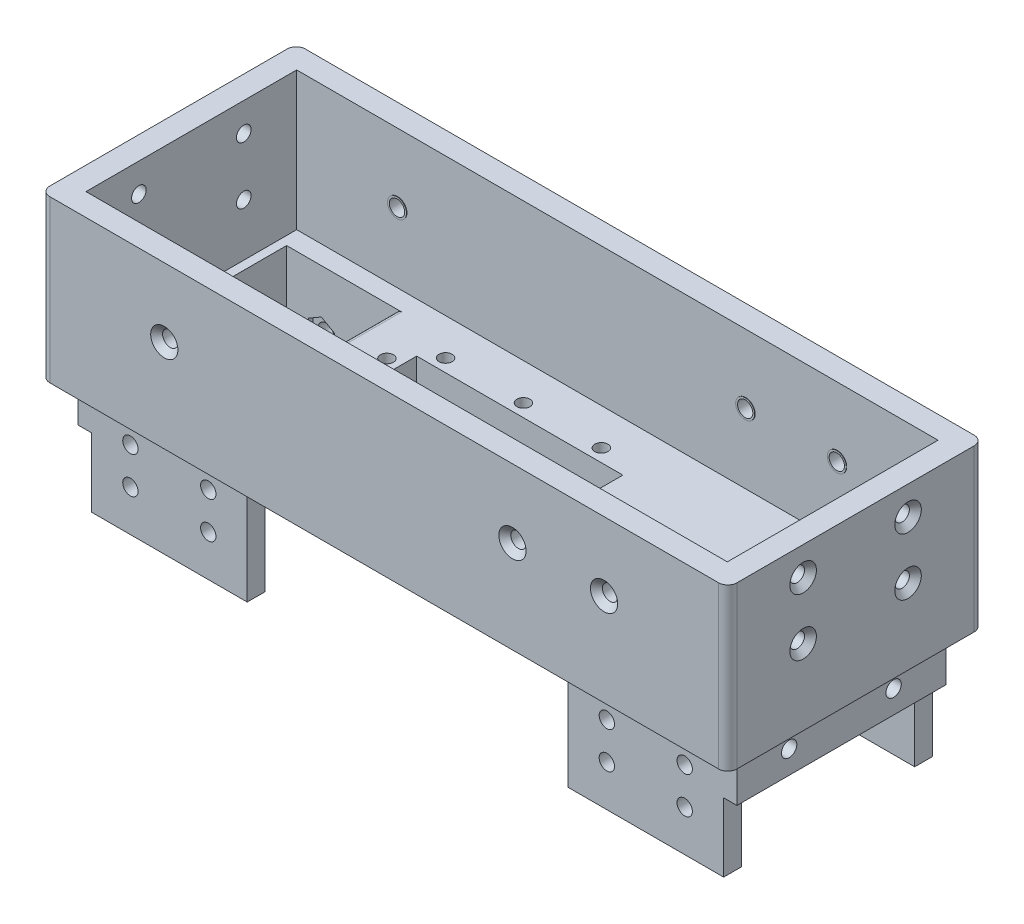
SolidWorks part; units mm, degrees
ref_plane "前视基准面" through (0, 0, 0) normal (0, 0, 1) x (1, 0, 0)
ref_plane "上视基准面" through (0, 0, 0) normal (0, 1, 0) x (1, 0, 0)
ref_plane "右视基准面" through (0, 0, 0) normal (1, 0, 0) x (0, 0, -1)
sketch "草图1" plane through (0, 0, 0) normal (0, 1, 0) x (1, 0, 0)
  line L1 (-75, 25.9) -> (75, 25.9)
  line L2 (-75, 25.9) -> (-75, -25.9)
  line L3 (-75, -25.9) -> (75, -25.9)
  line L4 (75, 25.9) -> (75, -25.9)
  line L5 (-75, 25.9) -> (75, -25.9) construction
  line L6 (-75, -25.9) -> (75, 25.9) construction
  line L7 (-70, 22.9) -> (70, 22.9)
  line L8 (-70, 22.9) -> (-70, -22.9)
  line L9 (-70, -22.9) -> (70, -22.9)
  line L10 (70, 22.9) -> (70, -22.9)
  line L11 (-70, 22.9) -> (70, -22.9) construction
  line L12 (-70, -22.9) -> (70, 22.9) construction
  point P0 (0, 0)
  point P5 (0, 0)
  dimension "D1" = 150
  dimension "D2" = 51.8
  dimension "D3" = 140
  dimension "D4" = 45.8
extrude "凸台-拉伸1" add sketch "草图1" along normal blind 35.2
sketch "草图2" plane through (0, 0, 0) normal (0, 1, 0) x (1, 0, 0)
  line L1 (-70, 22.9) -> (70, 22.9)
  line L2 (-70, 22.9) -> (-70, -22.9)
  line L3 (-70, -22.9) -> (70, -22.9)
  line L4 (70, 22.9) -> (70, -22.9)
  line L5 (-70, 22.9) -> (70, -22.9) construction
  line L6 (-70, -22.9) -> (70, 22.9) construction
  point P0 (0, 0)
extrude "凸台-拉伸2" add sketch "草图2" along normal blind 4.25 contours L1 L4 L3 L2
sketch "草图3" plane through (0, 0, 0) normal (0, 1, 0) x (1, 0, 0)
  line L1 (-33, 12.2) -> (12, 12.2)
  line L2 (-33, 12.2) -> (-33, -12.2)
  line L3 (-33, -12.2) -> (12, -12.2)
  line L4 (12, 12.2) -> (12, -12.2)
  dimension "D1" = 12
  dimension "D2" = 12.2
  dimension "D3" = 12.2
  dimension "D4" = 45
extrude "切除-拉伸2" cut sketch "草图3" along normal through all contours L3 L4 L1 L2
sketch "草图4" plane through (0, 0, 0) normal (0, 1, 0) x (1, 0, 0)
  circle A0 centre (4.5, 15) radius 1.425
  circle A1 centre (-12.5, 15) radius 1.425
  circle A2 centre (-29.5, 15) radius 1.425
  dimension "D1" = 2.85
  dimension "D2" = 2.85
  dimension "D3" = 2.85
extrude "切除-拉伸4" cut sketch "草图4" along normal through all
mirror "镜向1" about plane through (0, 0, 0) normal (0, 0, 1) of "切除-拉伸4"
ref_plane "基准面1" through (0, 0, -22.9) normal (0, 0, 1) x (1, 0, 0)
sketch "草图5" plane through (0, 0, -22.9) normal (0, 0, 1) x (1, 0, 0)
  line L0 (-70, 4.25) -> (-70, 35.2)
ref_plane "基准面2" through (0, 0, 0) normal (0, -1, 0) x (-1, 0, 0)
sketch "草图7" plane through (0, 0, 0) normal (0, -1, 0) x (-1, 0, 0)
  line L1 (-71.9, 22.8) -> (71.9, 22.8)
  line L2 (-71.9, 22.8) -> (-71.9, -22.8)
  line L3 (-71.9, -22.8) -> (71.9, -22.8)
  line L4 (71.9, 22.8) -> (71.9, -22.8)
  line L5 (-71.9, 22.8) -> (71.9, -22.8) construction
  line L6 (-71.9, -22.8) -> (71.9, 22.8) construction
  line L9 (-69, 19.9) -> (69, 19.9)
  line L10 (-69, 19.9) -> (-69, -19.9)
  line L11 (-69, -19.9) -> (69, -19.9)
  line L12 (69, 19.9) -> (69, -19.9)
  line L13 (-69, 19.9) -> (69, -19.9) construction
  line L14 (-69, -19.9) -> (69, 19.9) construction
  point P0 (0, 0)
  point P10 (0, 0)
  dimension "D1" = 2.9
  dimension "D2" = 2.9
  dimension "D3" = 138
  dimension "D4" = 39.8
  dimension "D5" = 143.8
extrude "凸台-拉伸3" add sketch "草图7" along normal blind 10
ref_plane "基准面3" through (0, 0, -22.8) normal (0, 0, -1) x (-1, 0, 0)
sketch "草图8" plane through (0, 0, -22.8) normal (0, 0, -1) x (-1, 0, 0)
  line L0 (0, 0) -> (35, 0)
  line L1 (-28.49, 0) -> (28.49, 0) construction
  line L2 (35, 0) -> (35, -10)
  line L3 (71.9, -10) -> (-71.9, -10) construction
  line L4 (35, -10) -> (-35, -10)
  line L5 (-35, -10) -> (-35, 0)
  line L6 (-35, 0) -> (0, 0)
  dimension "D1" = 35
  dimension "D2" = 35
extrude "切除-拉伸5" cut sketch "草图8" against normal through all
ref_plane "基准面4" through (0, 0, 0) normal (0, -1, 0) x (-1, 0, 0)
sketch "草图9" plane through (0, 0, 0) normal (0, -1, 0) x (-1, 0, 0)
  line L0 (-69, 19.9) -> (-69, -19.9)
  line L1 (-69, 19.9) -> (-69, -19.9) construction
  line L2 (-69, 19.9) -> (-69, -19.9) construction
  line L3 (-69, -19.9) -> (-44, -19.9)
  line L4 (-69, -19.9) -> (-35, -19.9) construction
  line L5 (-44, -19.9) -> (-44, 19.9)
  line L6 (-35, 19.9) -> (-69, 19.9) construction
  line L7 (-44, 19.9) -> (-69, 19.9)
  line L8 (69, 19.9) -> (44, 19.9)
  line L9 (69, 19.9) -> (35, 19.9) construction
  line L10 (44, 19.9) -> (44, -19.9)
  line L11 (35, -19.9) -> (69, -19.9) construction
  line L12 (44, -19.9) -> (69, -19.9)
  line L13 (69, -19.9) -> (69, 19.9)
extrude "切除-拉伸6" cut sketch "草图9" against normal blind 5
ref_plane "基准面5" through (0, 0, -22.9) normal (0, 0, 1) x (1, 0, 0)
sketch "草图10" plane through (0, 0, -22.9) normal (0, 0, 1) x (1, 0, 0)
  line L0 (48, 20.2) -> (28, 20.2)
  line L1 (-70, 35.2) -> (-70, 20.2)
  line L2 (-70, 35.2) -> (-70, 4.25) construction
  line L3 (-70, 20.2) -> (-26, 20.2)
  line L5 (-26, 20.2) -> (26, 20.2)
  line L6 (26, 20.2) -> (70, 20.2)
  line L7 (70, 35.2) -> (70, 4.25) construction
  circle A3 centre (48, 20.2) radius 1.675
  circle A5 centre (-48, 20.2) radius 1.675
  circle A6 centre (28, 20.2) radius 2.075
  point P13 (0, 20.2)
  dimension "D1" = 3.35
  dimension "D2" = 3.35
  dimension "D3" = 15
  dimension "D4" = 48
  dimension "D5" = 28
  dimension "D6" = 20
extrude "切除-拉伸8" cut sketch "草图10" against normal through all
mirror "镜向3" about plane through (0, 0, 0) normal (0, 0, 1) of "切除-拉伸8"
ref_plane "基准面6" through (75, 0, 0) normal (1, 0, 0) x (0, 0, -1)
sketch "草图11" plane through (75, 0, 0) normal (1, 0, 0) x (0, 0, -1)
  line L0 (-22.9, 35.2) -> (-22.9, 10.2)
  line L1 (-22.9, 10.2) -> (22.9, 10.2)
  line L2 (22.9, 17.0225) -> (22.9, -17.0225) construction
  line L3 (22.9, 10.2) -> (22.9, 35.2)
  line L4 (-25.9, 35.2) -> (25.9, 35.2) construction
  line L5 (22.9, 35.2) -> (-22.9, 35.2)
  line L6 (22.9, 10.2) -> (-22.9, 35.2)
  line L7 (0, 35.2) -> (0, 10.2)
  line L8 (0, 10.2) -> (-22.9, 22.7)
  line L9 (-22.9, 22.7) -> (0, 22.7)
  line L10 (0, 22.7) -> (22.9, 22.7)
  line L11 (22.9, 22.7) -> (22.9, 35.2)
  line L12 (0, 22.7) -> (22.9, 35.2)
  line L13 (-22.9, 35.2) -> (0, 22.7)
  line L14 (0, 22.7) -> (22.9, 10.2)
  circle A0 centre (-11.45, 16.45) radius 1.6
  circle A1 centre (-11.45, 28.95) radius 1.6
  circle A2 centre (11.45, 16.45) radius 1.6
  circle A3 centre (11.45, 28.95) radius 1.6
extrude "切除-拉伸10" cut sketch "草图11" against normal through all contours A0 | A1 | A3 | A2
ref_plane "基准面7" through (71.9, 0, 0) normal (1, 0, 0) x (0, 0, -1)
sketch "草图12" plane through (71.9, 0, 0) normal (1, 0, 0) x (0, 0, -1)
  line L0 (-22.8, 0) -> (-22.8, -10)
  line L1 (-22.8, -10) -> (22.8, -10)
  line L2 (22.8, -10) -> (22.8, 0)
  line L3 (22.8, 0) -> (-22.8, 0)
  line L4 (-22.8, 0) -> (0, -10)
  line L5 (0, -10) -> (22.8, 0)
  line L6 (0, 0) -> (22.8, -10)
  line L7 (-22.8, -10) -> (0, 0)
  circle A0 centre (-11.4, -5) radius 1.675
  circle A1 centre (11.4, -5) radius 1.675
  dimension "D1" = 3.35
  dimension "D2" = 3.35
extrude "切除-拉伸11" cut sketch "草图12" against normal through all contours A0 | A1
ref_plane "基准面8" through (0, 0, 22.8) normal (0, 0, 1) x (1, 0, 0)
sketch "草图14" plane through (-70, 0, 0) normal (1, 0, 0) x (0, 0, -1)
  line L0 (-22.9, 35.2) -> (-22.9, 4.25)
ref_plane "基准面9" through (0, 4.25, 0) normal (0, 1, 0) x (1, 0, 0)
sketch "草图17" plane through (0, 4.25, 0) normal (0, 1, 0) x (1, 0, 0)
  line L1 (-70, 22.9) -> (70, 22.9)
  line L2 (-70, 22.9) -> (-70, -22.9)
  line L3 (-70, -22.9) -> (70, -22.9)
  line L4 (70, 22.9) -> (70, -22.9)
  line L5 (-69, 19.9) -> (-44, 19.9)
  line L6 (-69, 19.9) -> (-69, -19.9)
  line L7 (-69, -19.9) -> (-44, -19.9)
  line L8 (-44, 19.9) -> (-44, -19.9)
  line L9 (-33, 12.2) -> (12, 12.2)
  line L10 (-33, 12.2) -> (-33, -12.2)
  line L11 (-33, -12.2) -> (12, -12.2)
  line L12 (12, 12.2) -> (12, -12.2)
  line L13 (44, 19.9) -> (69, 19.9)
  line L14 (44, 19.9) -> (44, -19.9)
  line L15 (44, -19.9) -> (69, -19.9)
  line L16 (69, 19.9) -> (69, -19.9)
  circle A0 centre (-29.5, 15) radius 1.425
  circle A1 centre (-12.5, 15) radius 1.425
  circle A2 centre (4.5, 15) radius 1.425
  circle A3 centre (4.5, -15) radius 1.425
  circle A4 centre (-12.5, -15) radius 1.425
  circle A5 centre (-29.5, -15) radius 1.425
  dimension "D1" = 2.85
  dimension "D2" = 2.85
  dimension "D3" = 2.85
  dimension "D4" = 2.85
  dimension "D5" = 2.85
  dimension "D6" = 2.85
extrude "凸台-拉伸4" add sketch "草图17" along normal blind 0.75
sketch "草图22" plane through (0, 0, -22.9) normal (0, 0, 1) x (1, 0, 0)
  circle A0 centre (28, 20.2) radius 1.675
  dimension "D1" = 3.35
extrude "切除-拉伸13" cut sketch "草图22" against normal through all
mirror "镜向4" about plane through (0, 0, 0) normal (0, 0, 1) of "切除-拉伸13"
sketch "草图26" plane through (0, 0, 22.9) normal (0, 0, -1) x (-1, 0, 0)
  line L1 (-70, 35.2) -> (70, 35.2)
  line L2 (-70, 35.2) -> (-70, 5)
  line L3 (-70, 5) -> (70, 5)
  line L4 (70, 35.2) -> (70, 5)
  circle A0 centre (48, 20.2) radius 2.075
  circle A1 centre (-28, 20.2) radius 2.075
  circle A2 centre (-48, 20.2) radius 2.075
extrude "切除-拉伸14" cut sketch "草图26" against normal blind 0.1
mirror "镜向5" about plane through (0, 0, 0) normal (0, 0, 1) of "切除-拉伸14"
sketch "草图29" plane through (0, 0, -25.9) normal (0, 0, -1) x (-1, 0, 0)
  line L0 (-75, 0) -> (75, 0) construction
  line L1 (-75, 35.2) -> (75, 35.2)
  line L2 (-75, 35.2) -> (-75, 0)
  line L3 (-75, 0) -> (75, 0)
  line L4 (75, 35.2) -> (75, 0)
  line L5 (75, 35.2) -> (75, 0) construction
  circle A0 centre (-28, 20.2) radius 1.675
  circle A1 centre (-48, 20.2) radius 1.675
  circle A2 centre (48, 20.2) radius 1.675
  dimension "D1" = 3.35
  dimension "D2" = 3.35
  dimension "D3" = 3.35
extrude "凸台-拉伸5" add sketch "草图29" along normal blind 2
mirror "镜向6" about plane through (0, 0, 0) normal (0, 0, 1) of "凸台-拉伸5"
sketch "草图32" plane through (71.9, 0, 0) normal (1, 0, 0) x (0, 0, -1)
  line L1 (-22.8, 0) -> (22.8, 0)
  line L2 (-22.8, 0) -> (-22.8, -10)
  line L3 (-22.8, -10) -> (22.8, -10)
  line L4 (22.8, 0) -> (22.8, -10)
  circle A0 centre (-11.4, -5) radius 1.6
  circle A1 centre (11.4, -5) radius 1.6
extrude "切除-拉伸15" cut sketch "草图32" against normal blind 0.1
mirror "镜向7" about plane through (0, 0, 0) normal (1, 0, 0) of "切除-拉伸15"
ref_plane "基准面10" through (0, -10, 0) normal (0, -1, 0) x (-1, 0, 0)
sketch "草图34" plane through (0, -10, 0) normal (0, -1, 0) x (-1, 0, 0)
  line L0 (69, 19.9) -> (35, 19.9) construction
  line L1 (-69, 19.9) -> (-35, 19.9)
  line L2 (-69, 19.9) -> (-69, 22.8)
  line L3 (-69, 22.8) -> (-35, 22.8)
  line L4 (-35, 19.9) -> (-35, 22.8)
  line L5 (35, 22.8) -> (69, 22.8)
  line L6 (35, 22.8) -> (35, 19.9)
  line L7 (35, 19.9) -> (69, 19.9)
  line L8 (69, 22.8) -> (69, 19.9)
  line L9 (35, -22.8) -> (71.8, -22.8) construction
  line L10 (35, -19.9) -> (69, -19.9)
  line L11 (35, -19.9) -> (35, -22.8)
  line L12 (35, -22.8) -> (69, -22.8)
  line L13 (69, -19.9) -> (69, -22.8)
  line L15 (-69, -19.9) -> (-35, -19.9)
  line L16 (-69, -19.9) -> (-69, -22.8)
  line L17 (-69, -22.8) -> (-35, -22.8)
  line L18 (-35, -19.9) -> (-35, -22.8)
  dimension "D1" = 34
extrude "凸台-拉伸6" add sketch "草图34" along normal blind 15
ref_plane "基准面11" through (0, 0, 22.8) normal (0, 0, 1) x (1, 0, 0)
sketch "草图43" plane through (0, 0, 22.8) normal (0, 0, 1) x (1, 0, 0)
  line L0 (69, -25) -> (69, -10) construction
  line L1 (35, 0) -> (69, 0)
  line L2 (35, 0) -> (35, -24.0026)
  line L3 (35, -24.0026) -> (69, -24.0026)
  line L4 (69, 0) -> (69, -24.0026)
  line L5 (35, 0) -> (35, -8.0014)
  line L6 (35, -8.0014) -> (35, -15.9991)
  line L7 (35, -15.9991) -> (69, -15.9991)
  line L8 (35, -8.0014) -> (69, -8.0014)
  line L9 (52, 0) -> (52, -24.0026)
  line L10 (35, 0) -> (52, -15.9991)
  line L11 (52, -15.9991) -> (52, -8.0014)
  line L12 (52, -8.0014) -> (35, -24.0026)
  line L13 (52, 0) -> (69, -15.9991)
  line L14 (69, -8.0014) -> (52, -24.0026)
  circle A0 centre (43.5, -7.9996) radius 1.675
  circle A1 centre (60.5, -7.9996) radius 1.675
  circle A2 centre (60.5, -16.002) radius 1.675
  circle A3 centre (43.5, -16.002) radius 1.675
  dimension "D1" = 3.35
  dimension "D2" = 3.35
  dimension "D3" = 3.35
  dimension "D4" = 3.35
extrude "切除-拉伸17" cut sketch "草图43" against normal through all contours A0 | A1 | A2 | A3
mirror "镜向9" about plane through (0, 0, 0) normal (1, 0, 0) of "切除-拉伸17"
fillet "圆角1" radius 2 4 edges at (75, 17.6, 27.9) (-75, 17.6, 27.9) (-75, 17.6, -27.9) (75, 17.6, -27.9)
fillet "圆角2" [suppressed] radius 1
ref_plane "基准面12" through (0, 0, 0) normal (0, -1, 0) x (-1, 0, 0)
sketch "草图44" plane through (0, 0, 0) normal (0, -1, 0) x (-1, 0, 0)
  line L0 (29.5, 15) -> (35.8, 15)
  line L1 (35.8, 15) -> (35.8, 8.5)
  line L2 (35.8, 8.5) -> (35.8, 0)
  line L3 (35.8, 0) -> (35.8, -8.5)
  line L4 (35.8, -8.5) -> (35.8, -15)
  line L5 (35.8, -15) -> (29.5, -15)
  circle A0 centre (35.8, -8.5) radius 1.425
  circle A1 centre (35.8, 8.5) radius 1.425
extrude "切除-拉伸18" cut sketch "草图44" against normal through all contours A1 | A0
sketch "草图48" plane through (0, 0, 22.9) normal (0, 0, -1) x (-1, 0, 0)
  circle A0 centre (-28, 20.2) radius 1.675
  circle A1 centre (-28, 20.2) radius 2.075
  circle A2 centre (-48, 20.2) radius 1.675
  circle A3 centre (-48, 20.2) radius 2.075
  circle A4 centre (48, 20.2) radius 1.675
  circle A5 centre (48, 20.2) radius 2.075
extrude "切除-拉伸19" cut sketch "草图48" against normal blind 0.1
chamfer "倒角1" distance 1.3 angle 45 4 edges at (75, 28.95, 9.85) (75, 16.45, 9.85) (75, 16.45, -13.05) (75, 28.95, -13.05)
chamfer "倒角2" distance 1.3 angle 45 10 edges at (-49.675, 20.2, -27.9) (26.325, 20.2, -27.9) (46.325, 20.2, -27.9) (46.325, 20.2, 27.9) (26.325, 20.2, 27.9) (-49.675, 20.2, 27.9) (-75, 16.45, 9.85) (-75, 16.45, -13.05) (-75, 28.95, 9.85) (-75, 28.95, -13.05)
sketch "草图51" plane through (0, 0, -19.9) normal (0, 0, 1) x (1, 0, 0)
  line L0 (-35, -25) -> (-35, 0)
  line L1 (-35, 0) -> (-44, 0)
  line L2 (-44, 0) -> (-44, 5)
  line L3 (-44, 5) -> (-69, 5)
  line L4 (-69, 5) -> (-69, -25)
  line L5 (-69, -25) -> (-35, -25)
  line L7 (-43.5, -12.7111) -> (-46.35, -14.3565)
  line L8 (-46.35, -14.3565) -> (-46.35, -17.6474)
  line L9 (-46.35, -17.6474) -> (-43.5, -19.2929)
  line L10 (-43.5, -19.2929) -> (-40.65, -17.6474)
  line L11 (-40.65, -17.6474) -> (-40.65, -14.3565)
  line L12 (-40.65, -14.3565) -> (-43.5, -12.7111)
  line L13 (-60.5, -12.7111) -> (-63.35, -14.3565)
  line L14 (-63.35, -14.3565) -> (-63.35, -17.6474)
  line L15 (-63.35, -17.6474) -> (-60.5, -19.2929)
  line L16 (-60.5, -19.2929) -> (-57.65, -17.6474)
  line L17 (-57.65, -17.6474) -> (-57.65, -14.3565)
  line L18 (-57.65, -14.3565) -> (-60.5, -12.7111)
  line L19 (-60.5, -4.7087) -> (-63.35, -6.3541)
  line L20 (-63.35, -6.3541) -> (-63.35, -9.645)
  line L21 (-63.35, -9.645) -> (-60.5, -11.2905)
  line L22 (-60.5, -11.2905) -> (-57.65, -9.645)
  line L23 (-57.65, -9.645) -> (-57.65, -6.3541)
  line L24 (-57.65, -6.3541) -> (-60.5, -4.7087)
  line L25 (-43.5, -4.7087) -> (-46.35, -6.3541)
  line L26 (-46.35, -6.3541) -> (-46.35, -9.645)
  line L27 (-46.35, -9.645) -> (-43.5, -11.2905)
  line L28 (-43.5, -11.2905) -> (-40.65, -9.645)
  line L29 (-40.65, -9.645) -> (-40.65, -6.3541)
  line L30 (-40.65, -6.3541) -> (-43.5, -4.7087)
  circle A0 centre (-43.5, -16.002) radius 1.675
  circle A1 centre (-60.5, -16.002) radius 1.675
  circle A2 centre (-60.5, -7.9996) radius 1.675
  circle A3 centre (-43.5, -7.9996) radius 1.675
  circle A4 centre (-43.5, -16.002) radius 2.85 construction
  circle A5 centre (-60.5, -16.002) radius 2.85 construction
  circle A6 centre (-60.5, -7.9996) radius 2.85 construction
  circle A7 centre (-43.5, -7.9996) radius 2.85 construction
  line M13 (-35, -25) -> (-35, 0)
  line M14 (-35, 0) -> (-44, 0)
  line M15 (-44, 0) -> (-44, 5)
  line M16 (-44, 5) -> (-69, 5)
  line M17 (-69, 5) -> (-69, -10)
  line M18 (-69, -10) -> (-69, -25)
  line M19 (-69, -25) -> (-35, -25)
  dimension "D1" = 5.7
  dimension "D2" = 5.7
  dimension "D3" = 5.7
  dimension "D4" = 5.7
extrude "凸台-拉伸7" add sketch "草图51" along normal blind 1 contours L30 L29 L28 L27 L26 L25 L24 L23 L22 L21 L20 L19 L18 L17 L16 L15 L14 L13 L12 L11 L10 L9 L8 L7 M19 M13 M14 M15 M16 M17 M18
mirror "镜向11" about plane through (0, 0, 0) normal (1, 0, 0) of "凸台-拉伸7"
mirror "镜向12" about plane through (0, 0, 0) normal (0, 0, 1) of "镜向11", "凸台-拉伸7"
sketch "草图52" plane through (-69, 0, 0) normal (1, 0, 0) x (0, 0, -1)
  line L0 (18.9, -10) -> (18.9, 5)
  line L1 (18.9, 5) -> (-18.9, 5)
  line L2 (18.9, 5) -> (-18.9, 5) construction
  line L3 (-18.9, 5) -> (-18.9, -10)
  line L4 (-18.9, -10) -> (18.9, -10)
  line L6 (11.4, -1.7087) -> (8.5496, -3.3543)
  line L7 (8.5496, -3.3543) -> (8.5496, -6.6457)
  line L8 (8.5496, -6.6457) -> (11.4, -8.2913)
  line L9 (11.4, -8.2913) -> (14.2504, -6.6457)
  line L10 (14.2504, -6.6457) -> (14.2504, -3.3543)
  line L11 (14.2504, -3.3543) -> (11.4, -1.7087)
  line L12 (-11.4, -1.7087) -> (-14.2504, -3.3543)
  line L13 (-14.2504, -3.3543) -> (-14.2504, -6.6457)
  line L14 (-14.2504, -6.6457) -> (-11.4, -8.2913)
  line L15 (-11.4, -8.2913) -> (-8.5496, -6.6457)
  line L16 (-8.5496, -6.6457) -> (-8.5496, -3.3543)
  line L17 (-8.5496, -3.3543) -> (-11.4, -1.7087)
  circle A0 centre (11.4, -5) radius 2.8504 construction
  circle A1 centre (-11.4, -5) radius 2.8504 construction
  dimension "D1" = 5.7007
  dimension "D2" = 5.7007
extrude "凸台-拉伸8" add sketch "草图52" along normal blind 0.9
mirror "镜向13" about plane through (0, 0, 0) normal (1, 0, 0) of "凸台-拉伸8"
sketch "草图57" plane through (-71.8, 0, 0) normal (-1, 0, 0) x (0, 0, 1)
  line L0 (22.8, -10) -> (-22.8, -10)
  line L1 (22.8, -10) -> (-22.8, -10) construction
  line L2 (-22.8, -10) -> (-22.8, 0)
  line L3 (-22.8, 0) -> (22.8, 0)
  line L4 (22.8, 0) -> (22.8, -10)
  circle A0 centre (11.4, -5) radius 1.675
  circle A1 centre (-11.4, -5) radius 1.675
extrude "凸台-拉伸9" add sketch "草图57" along normal blind 0.1
mirror "镜向14" about plane through (0, 0, 0) normal (1, 0, 0) of "凸台-拉伸9"
fillet "圆角3" radius 1 4 edges at (44, 5, 0) (44, 0, 0) (-44, 5, 0) (-44, 0, 0)
